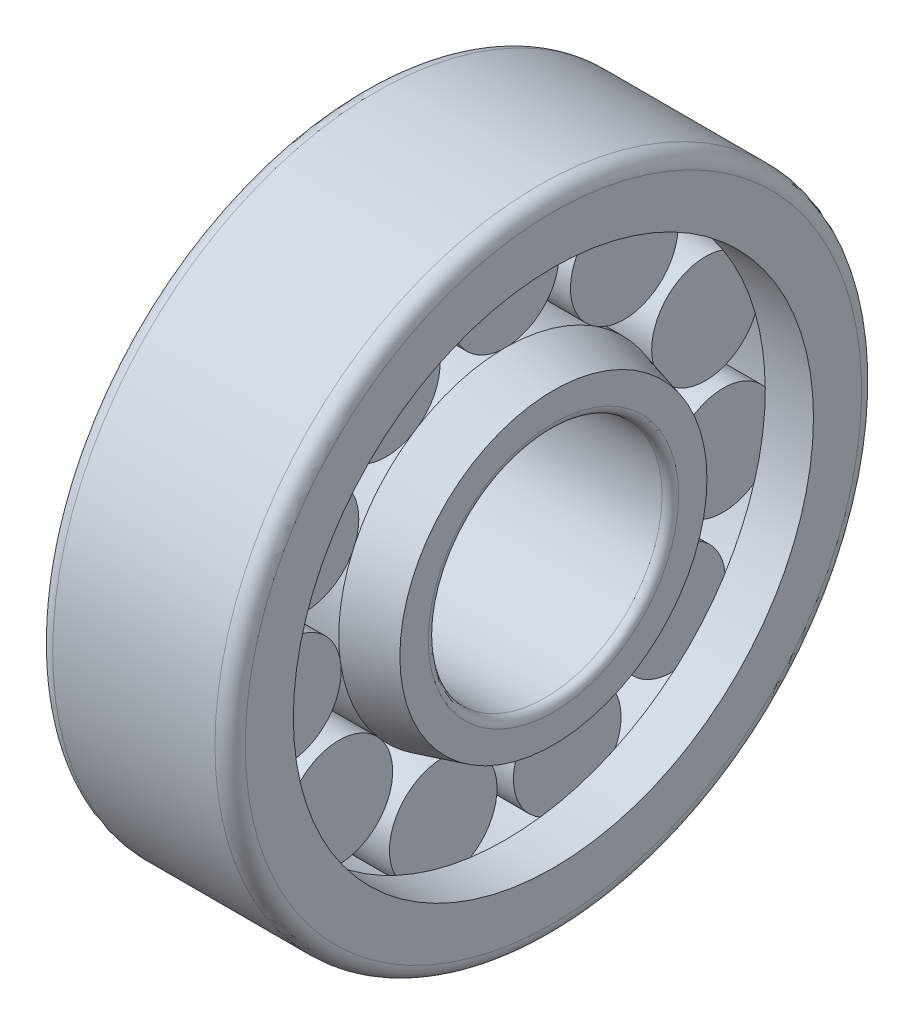
SolidWorks part; units mm, degrees
ref_plane "Front" through (0, 0, 0) normal (0, 0, 1) x (1, 0, 0)
ref_plane "Top" through (0, 0, 0) normal (0, 1, 0) x (1, 0, 0)
ref_plane "Right" through (0, 0, 0) normal (1, 0, 0) x (0, 0, -1)
other "Configuration Table"
sketch "Sketch1" plane through (0, 0, 0) normal (0, 0, 1) x (1, 0, 0)
  line L0 (-7, 8.5) -> (7, 8.5)
  line L1 (7, 8.5) -> (7, 11.1622)
  line L2 (7, 11.1622) -> (3.5, 12.1)
  line L3 (3.5, 12.1) -> (-3.5, 12.1)
  line L4 (-3.5, 12.1) -> (-7, 11.1622)
  line L5 (-7, 11.1622) -> (-7, 8.5)
  line L6 (-10.1379, 0) -> (10.5422, 0) construction
  dimension "D5" = 15
  dimension "D6" = 15
revolve "Revolve1" add sketch "Sketch1" angle 360 about L6
sketch "Sketch2" plane through (0, 0, 0) normal (0, 0, 1) x (1, 0, 0)
  line L0 (-3.5, 12.09) -> (3.5, 12.09)
  line L1 (3.5, 12.09) -> (3.5, 16)
  line L2 (-3.5, 16) -> (3.5, 16)
  line L3 (-3.5, 16) -> (-3.5, 12.09)
  line L4 (-7.1198, 0) -> (7.769, 0) construction
  line L6 (-7.4228, 16) -> (7.769, 16) construction
revolve "Revolve2" add sketch "Sketch2" angle 360 about L6
sketch "Sketch3" plane through (0, 0, 0) normal (0, 0, 1) x (1, 0, 0)
  line L0 (-7, 23.5) -> (7, 23.5)
  line L1 (7, 23.5) -> (7, 18.905)
  line L2 (7, 18.905) -> (3.49, 18.905)
  line L3 (3.49, 18.905) -> (3.49, 19.9)
  line L4 (3.49, 19.9) -> (-3.49, 19.9)
  line L5 (-3.49, 19.9) -> (-3.49, 18.905)
  line L6 (-3.49, 18.905) -> (-7, 18.905)
  line L7 (-7, 18.905) -> (-7, 23.5)
  line L8 (-9.0822, 0) -> (10.5352, 0) construction
  dimension "DD" = 47
revolve "Revolve3" add sketch "Sketch3" angle 360 about L8
pattern_circular "Circular-Pattern1" count 11 over 360 about axis through (0, 0, 0) along (1, 0, 0) of "Revolve2"
fillet "Fillet1" radius 1.1 2 edges at (-7, 0, 23.5) (7, 0, 23.5)
fillet "Fillet2" radius 0.6 2 edges at (7, 0, 8.5) (-7, 0, 8.5)
equation "\"D2@Sketch1\" = \"B@Sketch1\" / 2"
equation "\"D7@Sketch1\" = \"D2@Sketch1\""
equation "\"D8@Sketch1\" = \"D7@Sketch1\"/2"
equation "\"D2@Sketch2\" = ( \"DD@Sketch3\" + \"d@Sketch1\" )  / 4"
equation "\"D4@Sketch2\" = \"B@Sketch1\" / 2"
equation "\"D5@Sketch2\" = \"D4@Sketch2\" / 2"
equation "\"D1@Sketch2\" = \"FW@Sketch1\" - 0.02"
equation "\"B@Sketch3\" = \"B@Sketch1\""
equation "\"D5@Sketch3\" = \"B@Sketch3\" / 2"
equation "\"D6@Sketch3\" = \"D5@Sketch3\" - 0.02"
equation "\"D7@Sketch3\" = \"D6@Sketch3\" / 2"
equation "\"D2@Sketch3\" = ( \"DD@Sketch3\" + \"d@Sketch1\" )  / 4 * 2 + ( ( \"DD@Sketch3\" + \"d@Sketch1\" )  / 4 * 2 - \"FW@Sketch1\"  ) "
equation "\"D3@Sketch3\" = \"D2@Sketch3\" * 0.95"
equation "\"m@Circular-Pattern1\"=int(3.14159265/atn(((\"DD@Sketch3\"+\"d@Sketch1\")/4-\"FW@Sketch1\"/2+0.02) / sqr((\"DD@Sketch3\"+\"d@Sketch1\")/4  * (\"DD@Sketch3\"+\"d@Sketch1\")/4 - ((\"DD@Sketch3\"+\"d@Sketch1\")/4-\"FW@Sketch1\"/2+0.02) *  ((\"DD@Sketch3\"+\"d@Sketch1\")/4-\"FW@Sketch1\"/2+0.02))))-1"
